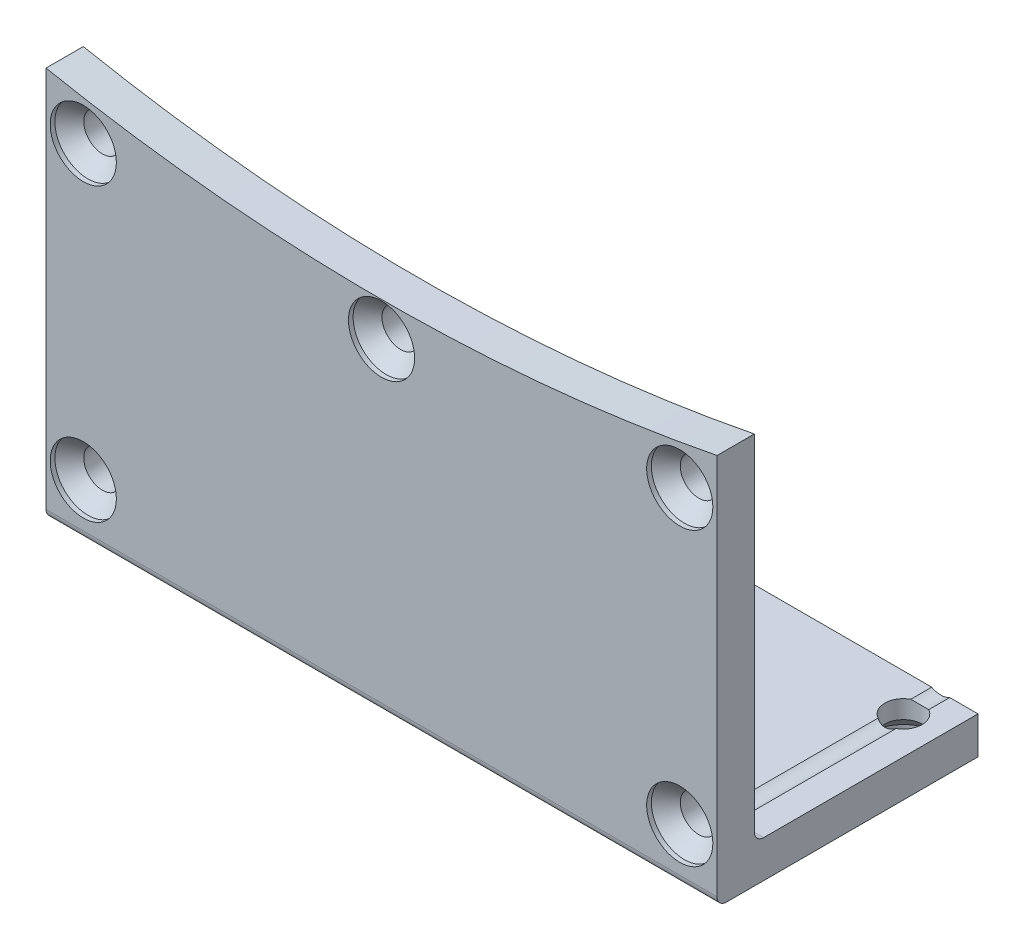
SolidWorks part; units mm, degrees
ref_plane "Plano frontal" through (0, 0, 0) normal (0, 0, 1) x (1, 0, 0)
ref_plane "Plano superior" through (0, 0, 0) normal (0, 1, 0) x (1, 0, 0)
ref_plane "Plano direito" through (0, 0, 0) normal (1, 0, 0) x (0, 0, -1)
sketch "Sketch1" plane through (0, 0, 0) normal (0, 0, 1) x (1, 0, 0)
  line L0 (36, -225) -> (36, -182.9925) construction
  line L1 (-36, -182.9925) -> (-36, -225) construction
  line L2 (36, -225) -> (36, -182.9925)
  line L3 (-36, -182.9925) -> (-36, -225)
  line L4 (-36, -225) -> (36, -225)
  arc A0 (-36, -182.9925) -> (36, -182.9925) centre (0, 0) ccw construction
  arc A1 (-36, -182.9925) -> (36, -182.9925) centre (0, 0) ccw
extrude "Boss-Extrude1" add sketch "Sketch1" against normal blind 4
sketch "Sketch2" plane through (0, 0, -4) normal (0, 0, -1) x (-1, 0, 0)
  line L0 (-36, -225) -> (-36, -182.9925) construction
  line L1 (36, -225) -> (-36, -225)
  line L2 (36, -225) -> (36, -221)
  line L3 (36, -221) -> (-36, -221)
  line L4 (-36, -225) -> (-36, -221)
  line L5 (36, -225) -> (-36, -221) construction
  line L6 (36, -221) -> (-36, -225) construction
  point P4 (0, -223)
  dimension "D1" = 4
extrude "Boss-Extrude2" add sketch "Sketch2" along normal up to surface (24 mm away)
hole_wizard "CSK for M4 Countersunk Flat Head Screw1" positions "Sketch6" profile "Sketch7" countersink size "M4" standard "ISO" end condition through all
sketch "Sketch6" plane through (0, 0, 0) normal (0, 0, 1) x (1, 0, 0)
  line L0 (-36, -182.9925) -> (-36, -225) construction
  line L1 (36, -225) -> (36, -182.9925) construction
  line L2 (0, 0) -> (0, -173.3359) construction
  line L4 (-36, -225) -> (36, -225) construction
  point P0 (-32, -219.25)
  point P2 (-32, -187.9925)
  point P4 (0, -190.1723)
  point P6 (32, -187.9925)
  point P8 (32, -219.25)
  dimension "D1" = 4
  dimension "D2" = 4
  dimension "D4" = 4
  dimension "D5" = 4
  dimension "D6" = 5
  dimension "D7" = 5
  dimension "D8" = 5.75
  dimension "D9" = 5.75
sketch "Sketch7" plane through (-32, -219.25, 0) normal (1, 0, 0) x (0, -1, 0)
  line L0 (0, 0) -> (0, 28)
  line L1 (0, 28) -> (2, 28)
  line L2 (2, 28) -> (2, 2.05)
  line L3 (2, 2.05) -> (3.55, 0.5)
  line L4 (3.55, 0.5) -> (3.55, 0)
  line L6 (3.55, 0) -> (0, 0)
  line L7 (-2, 2.05) -> (-3.55, 0.5) construction
  line L11 (0, -6.35) -> (0, 107.95) construction
  dimension "Thru Hole Dia." = 4
  dimension "Thru Hole Depth" = 28
  dimension "C'Sink Dia." = 7.1
  dimension "C'Sink Angle" = 90
  dimension "Head Clearance" = 0.5
hole_wizard "CSK for M4 Countersunk Flat Head Screw2" positions "Sketch8" profile "Sketch9" countersink size "M4" standard "ISO" end condition through all
sketch "Sketch8" plane through (0, -225, 0) normal (0, -1, 0) x (-1, 0, 0)
  line L0 (-36, 28) -> (-36, 0) construction
  line L1 (36, 28) -> (-36, 28) construction
  line L2 (36, 28) -> (36, 0) construction
  point P0 (-32, 24)
  point P2 (0, 24)
  point P4 (32, 24)
  dimension "D1" = 4
  dimension "D2" = 4
  dimension "D3" = 4
  dimension "D4" = 4
  dimension "D5" = 4
sketch "Sketch9" plane through (32, -225, -24) normal (1, 0, 0) x (0, 0, -1)
  line L0 (0, 0) -> (0, 42.0075)
  line L1 (0, 42.0075) -> (2, 42.0075)
  line L2 (2, 42.0075) -> (2, 2.05)
  line L3 (2, 2.05) -> (3.55, 0.5)
  line L4 (3.55, 0.5) -> (3.55, 0)
  line L6 (3.55, 0) -> (0, 0)
  line L7 (-2, 2.05) -> (-3.55, 0.5) construction
  line L11 (0, -6.35) -> (0, 107.95) construction
  dimension "Thru Hole Dia." = 4
  dimension "Thru Hole Depth" = 42.0075
  dimension "C'Sink Dia." = 7.1
  dimension "C'Sink Angle" = 90
  dimension "Head Clearance" = 0.5
fillet "Fillet1" radius 1 1 edges at (0, -225, 0)
fillet "Fillet2" radius 1 3 edges at (34.4841, -221, -4) (-34.4841, -221, -4) (0, -221, -4)
